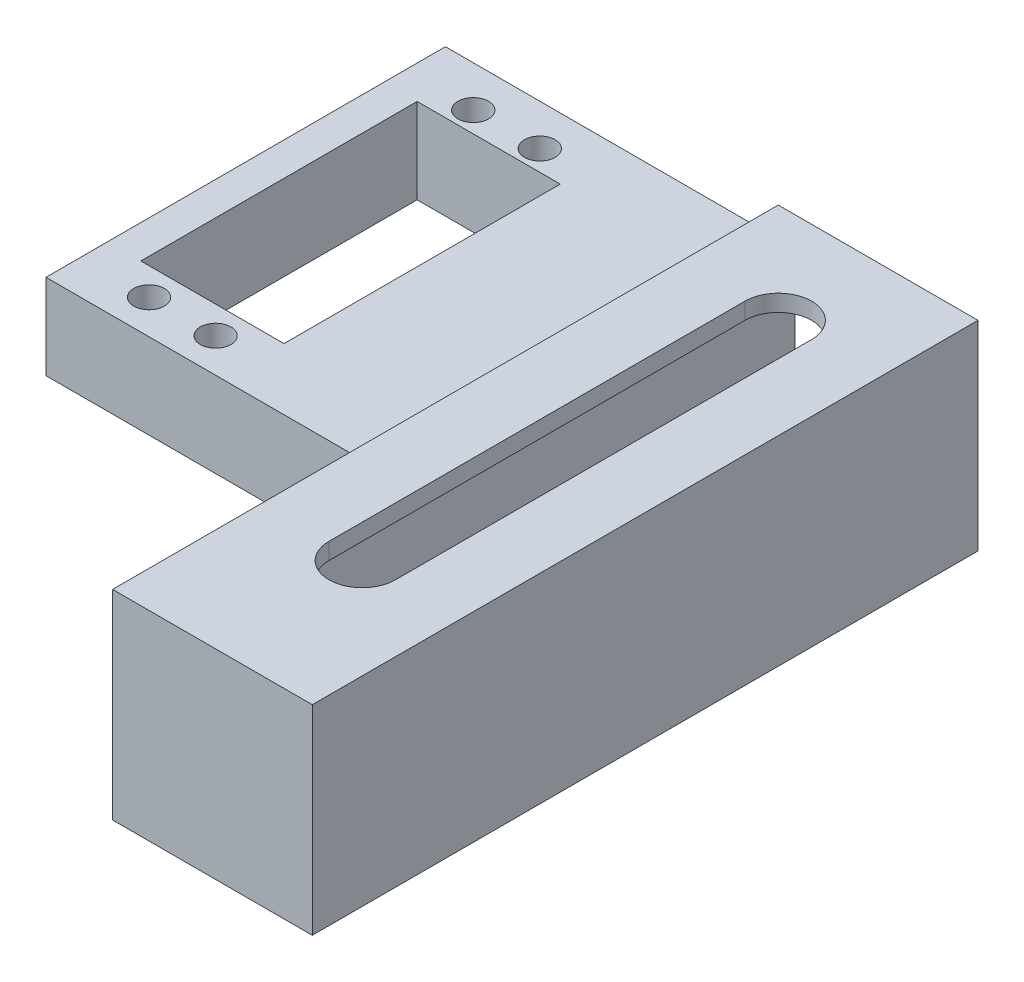
SolidWorks part; units mm, degrees
ref_plane "Front Plane" through (0, 0, 0) normal (0, 0, 1) x (1, 0, 0)
ref_plane "Top Plane" through (0, 0, 0) normal (0, 1, 0) x (1, 0, 0)
ref_plane "Right Plane" through (0, 0, 0) normal (1, 0, 0) x (0, 0, -1)
sketch "Esquisse1" plane through (0, 0, 0) normal (0, 0, 1) x (1, 0, 0)
  line L1 (0, 0) -> (-30, 0)
  line L2 (0, 0) -> (0, -30)
  line L3 (0, -30) -> (-30, -30)
  line L4 (-30, 0) -> (-30, -30)
  line L5 (-15, -30) -> (-15, 0) construction
  line L6 (0, -15) -> (-30, -15) construction
  point P432 (-15, -15)
  dimension "D1" = 30
extrude "Boss.-Extru.1" add sketch "Esquisse1" along normal blind 100
sketch "Esquisse2" plane through (0, 0, 0) normal (0, 0, -1) x (-1, 0, 0)
  line L0 (0, -30) -> (0, 0) construction
  line L1 (2.5, -2.5) -> (27.5, -2.5)
  line L2 (2.5, -2.5) -> (2.5, -27.5)
  line L3 (2.5, -27.5) -> (27.5, -27.5)
  line L4 (27.5, -2.5) -> (27.5, -27.5)
  line L5 (15, -27.5) -> (15, -2.5) construction
  line L6 (2.5, -15) -> (27.5, -15) construction
  line L7 (0, 0) -> (30, 0) construction
  point P6 (0, -15)
  point P11 (15, 0)
  point P152 (15, -15)
  dimension "D1" = 25
  dimension "D2" = 25
extrude "Enlèv. mat.-Extru.1" cut sketch "Esquisse2" against normal blind 95
sketch "Esquisse3" plane through (0, 0, 0) normal (0, 1, 0) x (1, 0, 0)
  line L0 (-15, 0) -> (-15, -100) construction
  line L1 (0, 0) -> (-30, 0) construction
  line L2 (0, -100) -> (-30, -100) construction
  line L3 (-15, -15) -> (-15, -77.5) construction
  line L4 (-10, -15) -> (-10, -77.5)
  line L5 (-20, -15) -> (-20, -77.5)
  arc A0 (-10, -15) -> (-20, -15) centre (-15, -15) ccw
  arc A1 (-20, -77.5) -> (-10, -77.5) centre (-15, -77.5) ccw
  point P8 (-15, -46.25)
  point P13 (-15, -82.5)
  point P15 (-15, -10)
  dimension "D1" = 82.5
  dimension "D2" = 10
  dimension "D3" = 10
extrude "Enlèv. mat.-Extru.2" cut sketch "Esquisse3" against normal up to surface (2.5 mm away) up to face at (-15, -2.5, 47.5)
sketch "Esquisse4" plane through (-30, 0, 0) normal (-1, 0, 0) x (0, 0, 1)
  line L0 (100, -30) -> (0, -30) construction
  line L1 (60, -4.4) -> (0, -4.4)
  line L2 (60, -4.4) -> (60, -30)
  line L3 (60, -30) -> (0, -30)
  line L4 (0, -4.4) -> (0, -30)
  line L5 (30, -30) -> (30, -4.4) construction
  line L6 (60, -17.2) -> (0, -17.2) construction
  line L11 (0, 0) -> (0, -30) construction
  point P124 (30, -17.2)
  dimension "D1" = 60
  dimension "D2" = 25.6
extrude "Boss.-Extru.2" add sketch "Esquisse4" along normal blind 50
sketch "Esquisse5" plane through (0, 0, 0) normal (0, 1, 0) x (1, 0, 0)
  line L0 (-80, 0) -> (-30, 0) construction
  line L1 (-75, -50.75) -> (-53.5, -50.75)
  line L2 (-75, -50.75) -> (-75, -9.25)
  line L3 (-75, -9.25) -> (-53.5, -9.25)
  line L4 (-53.5, -50.75) -> (-53.5, -9.25)
  line L5 (-64.25, -9.25) -> (-64.25, -50.75) construction
  line L6 (-75, -30) -> (-53.5, -30) construction
  line L8 (-80, -60) -> (-80, 0) construction
  point P100 (-64.25, -30)
  dimension "D1" = 41.5
  dimension "D2" = 21.5
  dimension "D3" = 5
  dimension "D4" = 9.25
extrude "Enlèv. mat.-Extru.3" cut sketch "Esquisse5" against normal through all
sketch "Esquisse6" plane through (0, 0, 0) normal (0, 1, 0) x (1, 0, 0)
  circle A4 centre (-69.66, -54.86) radius 2.3
  circle A5 centre (-59.66, -54.86) radius 2.3
  circle A6 centre (-69.66, -6.16) radius 2.3
  circle A7 centre (-59.66, -6.16) radius 2.3
extrude "Enlèv. mat.-Extru.4" cut sketch "Esquisse6" against normal through all
sketch "Esquisse9" plane through (0, 0, 0) normal (0, 0, -1) x (-1, 0, 0)
  line L1 (30, -17.2) -> (80, -17.2)
  line L2 (30, -17.2) -> (30, -30)
  line L3 (30, -30) -> (80, -30)
  line L4 (80, -17.2) -> (80, -30)
  line L5 (55, -30) -> (55, -17.2) construction
  line L6 (30, -23.6) -> (80, -23.6) construction
  line L7 (80, -4.4) -> (80, -30) construction
  line L8 (30, 0) -> (30, -4.4) construction
  point P6 (80, -17.2)
  point P116 (55, -23.6)
extrude "Enlèv. mat.-Extru.6" cut sketch "Esquisse9" against normal through all
